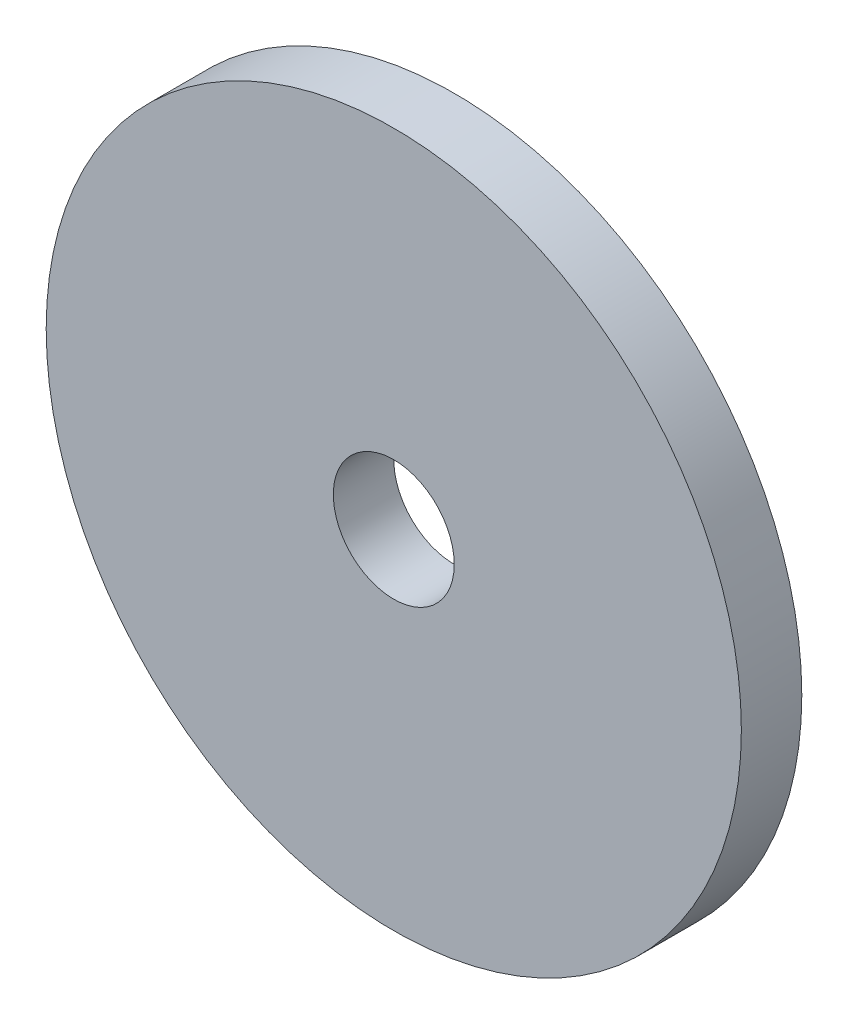
SolidWorks part; units mm, degrees
ref_plane "Front Plane" through (0, 0, 0) normal (0, 0, 1) x (1, 0, 0)
ref_plane "Top Plane" through (0, 0, 0) normal (0, 1, 0) x (1, 0, 0)
ref_plane "Right Plane" through (0, 0, 0) normal (1, 0, 0) x (0, 0, -1)
sketch "Sketch1" plane through (0, 0, 0) normal (0, 0, 1) x (1, 0, 0)
  circle A0 centre (0, 0) radius 5.75
  circle A1 centre (0, 0) radius 1
  dimension "D1" = 11.5
  dimension "D2" = 2
extrude "Boss-Extrude1" add sketch "Sketch1" along normal mid plane 1
